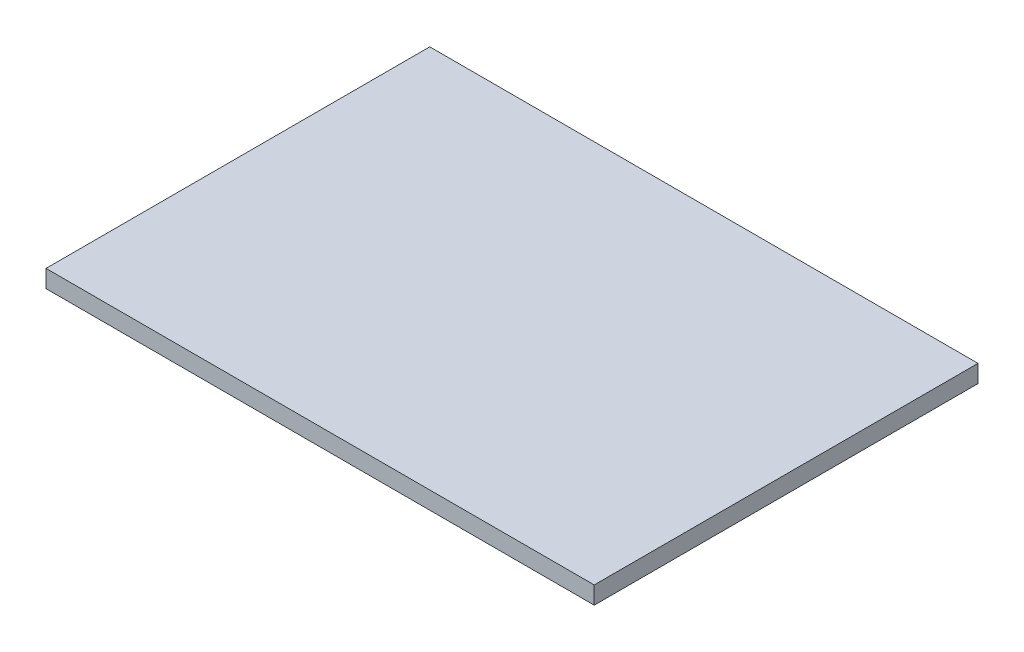
SolidWorks part; units mm, degrees
material "Balsa"
ref_plane "Front Plane" through (0, 0, 0) normal (0, 0, 1) x (1, 0, 0)
ref_plane "Top Plane" through (0, 0, 0) normal (0, 1, 0) x (1, 0, 0)
ref_plane "Right Plane" through (0, 0, 0) normal (1, 0, 0) x (0, 0, -1)
sketch "Sketch1" plane through (0, 0, 0) normal (0, 1, 0) x (1, 0, 0)
  line L0 (-125, -87.5) -> (125, 87.5) construction
  line L1 (-125, -87.5) -> (125, -87.5)
  line L2 (-125, -87.5) -> (-125, 87.5)
  line L3 (-125, 87.5) -> (125, 87.5)
  line L4 (125, -87.5) -> (125, 87.5)
  line L5 (-125, 87.5) -> (125, -87.5) construction
  point P4 (0, 0)
  dimension "D1" = 250
  dimension "D2" = 175
extrude "Boss-Extrude1" add sketch "Sketch1" along normal blind 8
